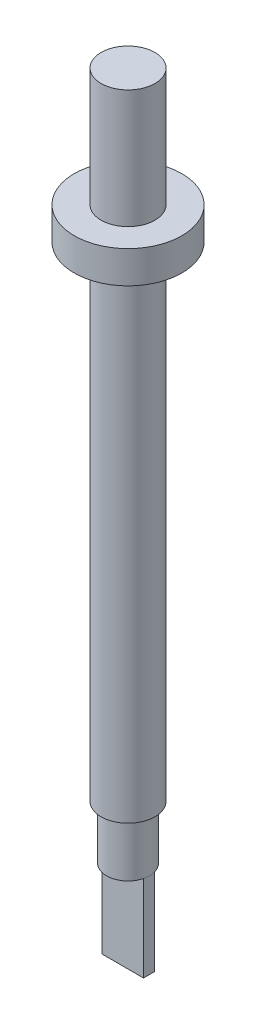
SolidWorks part; units mm, degrees
ref_plane "Front Plane" through (0, 0, 0) normal (0, 0, 1) x (1, 0, 0)
ref_plane "Top Plane" through (0, 0, 0) normal (0, 1, 0) x (1, 0, 0)
ref_plane "Right Plane" through (0, 0, 0) normal (1, 0, 0) x (0, 0, -1)
sketch "Sketch2" plane through (0, 0, 0) normal (0, 0, 1) x (1, 0, 0)
  line L0 (0, 0) -> (0, 50)
  line L1 (2, 0) -> (2, 5)
  line L2 (2, 5) -> (2.5, 5)
  line L3 (2.5, 5) -> (2.5, 50)
  line L5 (0, 0) -> (2, 0)
  line L10 (0, 50) -> (0, 53)
  line L11 (0, 53) -> (5, 53)
  line L12 (5, 53) -> (5, 50)
  line L13 (5, 50) -> (2.5, 50)
  dimension "D1" = 50
  dimension "D2" = 2.5
  dimension "D3" = 2
  dimension "D4" = 5
  dimension "D5" = 3
  dimension "D6" = 45
  dimension "D7" = 5
revolve "Revolve1" add sketch "Sketch2" angle 360 about L0
sketch "Sketch4" plane through (0, 0, 0) normal (0, -1, 0) x (1, 0, 0)
  line L0 (-1.9365, 0) -> (1.9365, 0) construction
  line L1 (-1.9365, 0.5) -> (1.9365, 0.5)
  line L2 (-1.9365, 0.5) -> (-1.9365, -0.5)
  line L3 (-1.9365, -0.5) -> (1.9365, -0.5)
  line L4 (1.9365, 0.5) -> (1.9365, -0.5)
  line L5 (0, 0.5) -> (0, -0.5) construction
  circle A0 centre (0, 0) radius 2 construction
  dimension "D1" = 1
extrude "Boss-Extrude1" add sketch "Sketch4" along normal blind 8
sketch "Sketch5" plane through (0, 53, 0) normal (0, 1, 0) x (1, 0, 0)
  circle A0 centre (0, 0) radius 2.5
  dimension "D1" = 5
extrude "Boss-Extrude2" add sketch "Sketch5" along normal blind 11
